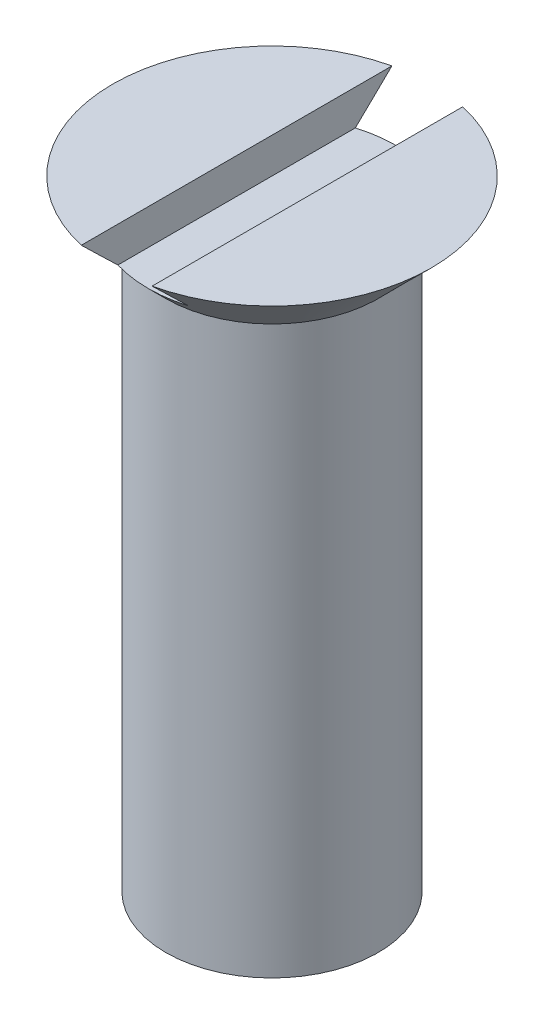
SolidWorks part; units mm, degrees
ref_plane "Front Plane" through (0, 0, 0) normal (0, 0, 1) x (1, 0, 0)
ref_plane "Top Plane" through (0, 0, 0) normal (0, 1, 0) x (1, 0, 0)
ref_plane "Right Plane" through (0, 0, 0) normal (1, 0, 0) x (0, 0, -1)
sketch "Sketch1" plane through (0, 0, 0) normal (0, 0, 1) x (1, 0, 0)
  line L0 (0, 0) -> (-4.5, 0)
  line L1 (-4.5, 0) -> (-3, -1.5)
  line L2 (0, 0) -> (0, -17.5)
  line L3 (0, -17.5) -> (0, -19.2321)
  line L4 (-3, -17.5) -> (-3, -1.5)
  line L5 (0, -19.2321) -> (-3, -17.5)
  dimension "D1" = 3
  dimension "D2" = 4.5
  dimension "D3" = 45
  dimension "D4" = 16
  dimension "D5" = 60
revolve "Revolve1" add sketch "Sketch1" angle 360 about L2
cosmetic thread "Cosmetic Thread1"
cosmetic thread "Cosmetic Thread2"
cosmetic thread "Cosmetic Thread3"
cosmetic thread "Cosmetic Thread4"
cosmetic thread "Cosmetic Thread5"
sketch "Sketch2" plane through (0, 0, 0) normal (0, 1, 0) x (1, 0, 0)
  line L1 (-1, 4.8915) -> (1, 4.8915)
  line L2 (-1, 4.8915) -> (-1, -4.9061)
  line L3 (-1, -4.9061) -> (1, -4.9061)
  line L4 (1, 4.8915) -> (1, -4.9061)
  dimension "D2" = 1
  dimension "D1" = 2
extrude "Extrude1" cut sketch "Sketch2" against normal blind 1
